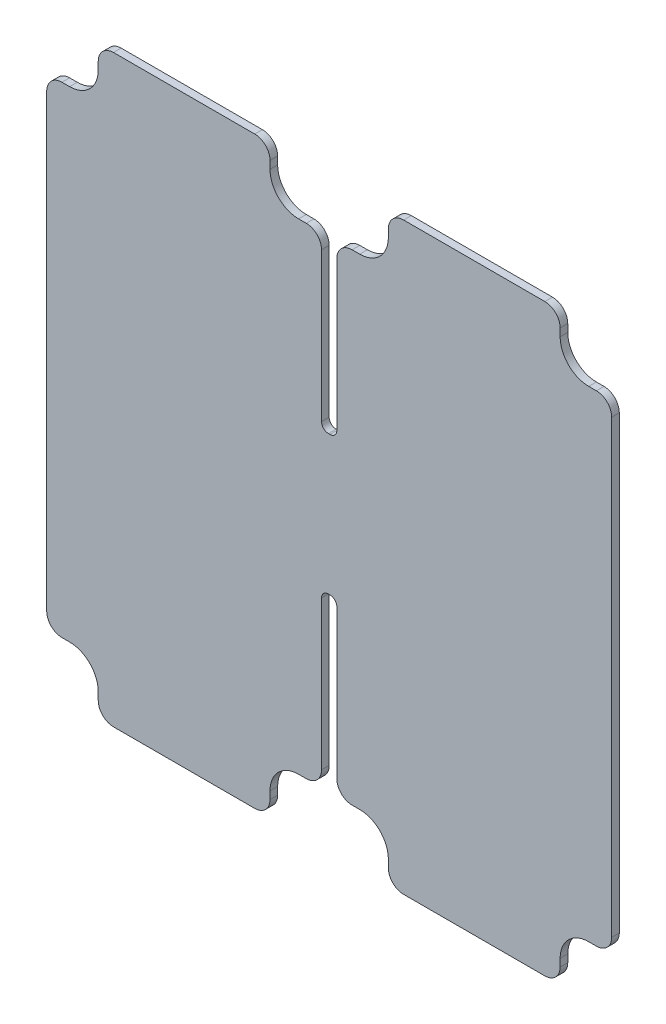
SolidWorks part; units mm, degrees
ref_plane "Front Plane" through (0, 0, 0) normal (0, 0, 1) x (1, 0, 0)
ref_plane "Top Plane" through (0, 0, 0) normal (0, 1, 0) x (1, 0, 0)
ref_plane "Right Plane" through (0, 0, 0) normal (1, 0, 0) x (0, 0, -1)
sketch "Model" plane through (0, 0, 0) normal (0, 0, 1) x (1, 0, 0)
  line L0 (3, 69.75) -> (2, 69.75)
  line L1 (6.75, 74.5) -> (6.75, 73.5)
  line L2 (29.25, 73.5) -> (29.25, 74.5)
  line L3 (34, 69.75) -> (33, 69.75)
  line L4 (33, 6.75) -> (34, 6.75)
  line L5 (29.25, 2) -> (29.25, 3)
  line L6 (6.75, 3) -> (6.75, 2)
  line L7 (2, 6.75) -> (3, 6.75)
  line L8 (36, 8.75) -> (36, 67.75)
  line L9 (8.75, 0) -> (27.25, 0)
  line L10 (0, 67.75) -> (0, 8.75)
  line L11 (27.25, 76.5) -> (8.75, 76.5)
  line L12 (41, 69.75) -> (40, 69.75)
  line L13 (44.75, 74.5) -> (44.75, 73.5)
  line L14 (67.25, 73.5) -> (67.25, 74.5)
  line L15 (72, 69.75) -> (71, 69.75)
  line L16 (71, 6.75) -> (72, 6.75)
  line L17 (67.25, 2) -> (67.25, 3)
  line L18 (44.75, 3) -> (44.75, 2)
  line L19 (40, 6.75) -> (41, 6.75)
  line L20 (74, 8.75) -> (74, 67.75)
  line L21 (46.75, 0) -> (65.25, 0)
  line L22 (38, 67.75) -> (38, 8.75)
  line L23 (65.25, 76.5) -> (46.75, 76.5)
  arc A0 (2, 69.7525) -> (2, 69.7475) centre (2, 69.75) ccw
  arc A1 (3, 69.7475) -> (3, 69.7525) centre (3, 69.75) ccw
  arc A2 (6.7475, 73.5) -> (6.7525, 73.5) centre (6.75, 73.5) ccw
  arc A3 (6.7525, 74.5) -> (6.7475, 74.5) centre (6.75, 74.5) ccw
  arc A4 (29.2525, 74.5) -> (29.2475, 74.5) centre (29.25, 74.5) ccw
  arc A5 (29.2475, 73.5) -> (29.2525, 73.5) centre (29.25, 73.5) ccw
  arc A6 (33, 69.7525) -> (33, 69.7475) centre (33, 69.75) ccw
  arc A7 (34, 69.7475) -> (34, 69.7525) centre (34, 69.75) ccw
  arc A8 (34, 6.7475) -> (34, 6.7525) centre (34, 6.75) ccw
  arc A9 (33, 6.7525) -> (33, 6.7475) centre (33, 6.75) ccw
  arc A10 (29.2525, 3) -> (29.2475, 3) centre (29.25, 3) ccw
  arc A11 (29.2475, 2) -> (29.2525, 2) centre (29.25, 2) ccw
  arc A12 (6.7475, 2) -> (6.7525, 2) centre (6.75, 2) ccw
  arc A13 (6.7525, 3) -> (6.7475, 3) centre (6.75, 3) ccw
  arc A14 (3, 6.7475) -> (3, 6.7525) centre (3, 6.75) ccw
  arc A15 (2, 6.7525) -> (2, 6.7475) centre (2, 6.75) ccw
  arc A16 (36.0025, 67.75) -> (35.9975, 67.75) centre (36, 67.75) ccw
  arc A17 (35.9975, 8.75) -> (36.0025, 8.75) centre (36, 8.75) ccw
  arc A18 (27.25, -0.0025) -> (27.25, 0.0025) centre (27.25, 0) ccw
  arc A19 (8.75, 0.0025) -> (8.75, -0.0025) centre (8.75, 0) ccw
  arc A20 (-0.0025, 8.75) -> (0.0025, 8.75) centre (0, 8.75) ccw
  arc A21 (0.0025, 67.75) -> (-0.0025, 67.75) centre (0, 67.75) ccw
  arc A22 (8.75, 76.5025) -> (8.75, 76.4975) centre (8.75, 76.5) ccw
  arc A23 (27.25, 76.4975) -> (27.25, 76.5025) centre (27.25, 76.5) ccw
  arc A24 (2, 69.75) -> (0, 67.75) centre (2, 67.75) ccw
  arc A25 (2, 69.7475) -> (2, 69.7525) centre (2, 69.75) ccw
  arc A26 (-0.0025, 67.75) -> (0.0025, 67.75) centre (0, 67.75) ccw
  arc A27 (3, 69.75) -> (6.75, 73.5) centre (2.9999, 73.5001) ccw
  arc A28 (3, 69.7525) -> (3, 69.7475) centre (3, 69.75) ccw
  arc A29 (6.7525, 73.5) -> (6.7475, 73.5) centre (6.75, 73.5) ccw
  arc A30 (8.75, 76.5) -> (6.75, 74.5) centre (8.75, 74.5) ccw
  arc A31 (8.75, 76.4975) -> (8.75, 76.5025) centre (8.75, 76.5) ccw
  arc A32 (6.7475, 74.5) -> (6.7525, 74.5) centre (6.75, 74.5) ccw
  arc A33 (29.25, 74.5) -> (27.25, 76.5) centre (27.25, 74.5) ccw
  arc A34 (29.2475, 74.5) -> (29.2525, 74.5) centre (29.25, 74.5) ccw
  arc A35 (27.25, 76.5025) -> (27.25, 76.4975) centre (27.25, 76.5) ccw
  arc A36 (29.25, 73.5) -> (33, 69.75) centre (33.0001, 73.5001) ccw
  arc A37 (29.2525, 73.5) -> (29.2475, 73.5) centre (29.25, 73.5) ccw
  arc A38 (33, 69.7475) -> (33, 69.7525) centre (33, 69.75) ccw
  arc A39 (36, 67.75) -> (34, 69.75) centre (34, 67.75) ccw
  arc A40 (35.9975, 67.75) -> (36.0025, 67.75) centre (36, 67.75) ccw
  arc A41 (34, 69.7525) -> (34, 69.7475) centre (34, 69.75) ccw
  arc A42 (34, 6.75) -> (36, 8.75) centre (34, 8.75) ccw
  arc A43 (34, 6.7525) -> (34, 6.7475) centre (34, 6.75) ccw
  arc A44 (36.0025, 8.75) -> (35.9975, 8.75) centre (36, 8.75) ccw
  arc A45 (33, 6.75) -> (29.25, 3) centre (33.0001, 2.9999) ccw
  arc A46 (33, 6.7475) -> (33, 6.7525) centre (33, 6.75) ccw
  arc A47 (29.2475, 3) -> (29.2525, 3) centre (29.25, 3) ccw
  arc A48 (27.25, 0) -> (29.25, 2) centre (27.25, 2) ccw
  arc A49 (27.25, 0.0025) -> (27.25, -0.0025) centre (27.25, 0) ccw
  arc A50 (29.2525, 2) -> (29.2475, 2) centre (29.25, 2) ccw
  arc A51 (6.75, 2) -> (8.75, 0) centre (8.75, 2) ccw
  arc A52 (6.7525, 2) -> (6.7475, 2) centre (6.75, 2) ccw
  arc A53 (8.75, -0.0025) -> (8.75, 0.0025) centre (8.75, 0) ccw
  arc A54 (6.75, 3) -> (3, 6.75) centre (2.9999, 2.9999) ccw
  arc A55 (6.7475, 3) -> (6.7525, 3) centre (6.75, 3) ccw
  arc A56 (3, 6.7525) -> (3, 6.7475) centre (3, 6.75) ccw
  arc A57 (0, 8.75) -> (2, 6.75) centre (2, 8.75) ccw
  arc A58 (0.0025, 8.75) -> (-0.0025, 8.75) centre (0, 8.75) ccw
  arc A59 (2, 6.7475) -> (2, 6.7525) centre (2, 6.75) ccw
  arc A60 (40, 69.7525) -> (40, 69.7475) centre (40, 69.75) ccw
  arc A61 (41, 69.7475) -> (41, 69.7525) centre (41, 69.75) ccw
  arc A62 (44.7475, 73.5) -> (44.7525, 73.5) centre (44.75, 73.5) ccw
  arc A63 (44.7525, 74.5) -> (44.7475, 74.5) centre (44.75, 74.5) ccw
  arc A64 (67.2525, 74.5) -> (67.2475, 74.5) centre (67.25, 74.5) ccw
  arc A65 (67.2475, 73.5) -> (67.2525, 73.5) centre (67.25, 73.5) ccw
  arc A66 (71, 69.7525) -> (71, 69.7475) centre (71, 69.75) ccw
  arc A67 (72, 69.7475) -> (72, 69.7525) centre (72, 69.75) ccw
  arc A68 (72, 6.7475) -> (72, 6.7525) centre (72, 6.75) ccw
  arc A69 (71, 6.7525) -> (71, 6.7475) centre (71, 6.75) ccw
  arc A70 (67.2525, 3) -> (67.2475, 3) centre (67.25, 3) ccw
  arc A71 (67.2475, 2) -> (67.2525, 2) centre (67.25, 2) ccw
  arc A72 (44.7475, 2) -> (44.7525, 2) centre (44.75, 2) ccw
  arc A73 (44.7525, 3) -> (44.7475, 3) centre (44.75, 3) ccw
  arc A74 (41, 6.7475) -> (41, 6.7525) centre (41, 6.75) ccw
  arc A75 (40, 6.7525) -> (40, 6.7475) centre (40, 6.75) ccw
  arc A76 (74.0025, 67.75) -> (73.9975, 67.75) centre (74, 67.75) ccw
  arc A77 (73.9975, 8.75) -> (74.0025, 8.75) centre (74, 8.75) ccw
  arc A78 (65.25, -0.0025) -> (65.25, 0.0025) centre (65.25, 0) ccw
  arc A79 (46.75, 0.0025) -> (46.75, -0.0025) centre (46.75, 0) ccw
  arc A80 (37.9975, 8.75) -> (38.0025, 8.75) centre (38, 8.75) ccw
  arc A81 (38.0025, 67.75) -> (37.9975, 67.75) centre (38, 67.75) ccw
  arc A82 (46.75, 76.5025) -> (46.75, 76.4975) centre (46.75, 76.5) ccw
  arc A83 (65.25, 76.4975) -> (65.25, 76.5025) centre (65.25, 76.5) ccw
  arc A84 (40, 69.75) -> (38, 67.75) centre (40, 67.75) ccw
  arc A85 (40, 69.7475) -> (40, 69.7525) centre (40, 69.75) ccw
  arc A86 (37.9975, 67.75) -> (38.0025, 67.75) centre (38, 67.75) ccw
  arc A87 (41, 69.75) -> (44.75, 73.5) centre (40.9999, 73.5001) ccw
  arc A88 (41, 69.7525) -> (41, 69.7475) centre (41, 69.75) ccw
  arc A89 (44.7525, 73.5) -> (44.7475, 73.5) centre (44.75, 73.5) ccw
  arc A90 (46.75, 76.5) -> (44.75, 74.5) centre (46.75, 74.5) ccw
  arc A91 (46.75, 76.4975) -> (46.75, 76.5025) centre (46.75, 76.5) ccw
  arc A92 (44.7475, 74.5) -> (44.7525, 74.5) centre (44.75, 74.5) ccw
  arc A93 (67.25, 74.5) -> (65.25, 76.5) centre (65.25, 74.5) ccw
  arc A94 (67.2475, 74.5) -> (67.2525, 74.5) centre (67.25, 74.5) ccw
  arc A95 (65.25, 76.5025) -> (65.25, 76.4975) centre (65.25, 76.5) ccw
  arc A96 (67.25, 73.5) -> (71, 69.75) centre (71.0001, 73.5001) ccw
  arc A97 (67.2525, 73.5) -> (67.2475, 73.5) centre (67.25, 73.5) ccw
  arc A98 (71, 69.7475) -> (71, 69.7525) centre (71, 69.75) ccw
  arc A99 (74, 67.75) -> (72, 69.75) centre (72, 67.75) ccw
  arc A100 (73.9975, 67.75) -> (74.0025, 67.75) centre (74, 67.75) ccw
  arc A101 (72, 69.7525) -> (72, 69.7475) centre (72, 69.75) ccw
  arc A102 (72, 6.75) -> (74, 8.75) centre (72, 8.75) ccw
  arc A103 (72, 6.7525) -> (72, 6.7475) centre (72, 6.75) ccw
  arc A104 (74.0025, 8.75) -> (73.9975, 8.75) centre (74, 8.75) ccw
  arc A105 (71, 6.75) -> (67.25, 3) centre (71.0001, 2.9999) ccw
  arc A106 (71, 6.7475) -> (71, 6.7525) centre (71, 6.75) ccw
  arc A107 (67.2475, 3) -> (67.2525, 3) centre (67.25, 3) ccw
  arc A108 (65.25, 0) -> (67.25, 2) centre (65.25, 2) ccw
  arc A109 (65.25, 0.0025) -> (65.25, -0.0025) centre (65.25, 0) ccw
  arc A110 (67.2525, 2) -> (67.2475, 2) centre (67.25, 2) ccw
  arc A111 (44.75, 2) -> (46.75, 0) centre (46.75, 2) ccw
  arc A112 (44.7525, 2) -> (44.7475, 2) centre (44.75, 2) ccw
  arc A113 (46.75, -0.0025) -> (46.75, 0.0025) centre (46.75, 0) ccw
  arc A114 (44.75, 3) -> (41, 6.75) centre (40.9999, 2.9999) ccw
  arc A115 (44.7475, 3) -> (44.7525, 3) centre (44.75, 3) ccw
  arc A116 (41, 6.7525) -> (41, 6.7475) centre (41, 6.75) ccw
  arc A117 (38, 8.75) -> (40, 6.75) centre (40, 8.75) ccw
  arc A118 (38.0025, 8.75) -> (37.9975, 8.75) centre (38, 8.75) ccw
  arc A119 (40, 6.7475) -> (40, 6.7525) centre (40, 6.75) ccw
sketch "Sketch2" plane through (0, 0, 0) normal (0, 0, 1) x (1, 0, 0)
  line L0 (36, 8.75) -> (36, 67.75) construction
  line L1 (38, 67.75) -> (38, 8.75) construction
  line L2 (41, 69.75) -> (40, 69.75) construction
  line L3 (44.75, 74.5) -> (44.75, 73.5) construction
  line L4 (65.25, 76.5) -> (46.75, 76.5) construction
  line L5 (67.25, 73.5) -> (67.25, 74.5) construction
  line L6 (72, 69.75) -> (71, 69.75) construction
  line L7 (74, 8.75) -> (74, 67.75) construction
  line L8 (33, 6.75) -> (34, 6.75) construction
  line L9 (40, 6.75) -> (41, 6.75) construction
  line L10 (44.75, 3) -> (44.75, 2) construction
  line L11 (46.75, 0) -> (65.25, 0) construction
  line L12 (67.25, 2) -> (67.25, 3) construction
  line L13 (71, 6.75) -> (72, 6.75) construction
  line L14 (29.25, 2) -> (29.25, 3) construction
  line L15 (8.75, 0) -> (27.25, 0) construction
  line L16 (6.75, 3) -> (6.75, 2) construction
  line L17 (2, 6.75) -> (3, 6.75) construction
  line L18 (34, 69.75) -> (33, 69.75) construction
  line L19 (29.25, 73.5) -> (29.25, 74.5) construction
  line L20 (27.25, 76.5) -> (8.75, 76.5) construction
  line L21 (6.75, 74.5) -> (6.75, 73.5) construction
  line L22 (3, 69.75) -> (2, 69.75) construction
  line L23 (0, 67.75) -> (0, 8.75) construction
  line L24 (36, 8.75) -> (36, 67.75) construction
  line L25 (38, 67.75) -> (38, 8.75) construction
  line L26 (41, 69.75) -> (40, 69.75)
  line L27 (44.75, 74.5) -> (44.75, 73.5)
  line L28 (65.25, 76.5) -> (46.75, 76.5)
  line L29 (67.25, 73.5) -> (67.25, 74.5)
  line L30 (72, 69.75) -> (71, 69.75)
  line L31 (74, 8.75) -> (74, 67.75)
  line L32 (33, 6.75) -> (34, 6.75)
  line L33 (40, 6.75) -> (41, 6.75)
  line L34 (44.75, 3) -> (44.75, 2)
  line L35 (46.75, 0) -> (65.25, 0)
  line L36 (67.25, 2) -> (67.25, 3)
  line L37 (71, 6.75) -> (72, 6.75)
  line L38 (29.25, 2) -> (29.25, 3)
  line L39 (8.75, 0) -> (27.25, 0)
  line L40 (6.75, 3) -> (6.75, 2)
  line L41 (2, 6.75) -> (3, 6.75)
  line L42 (34, 69.75) -> (33, 69.75)
  line L43 (29.25, 73.5) -> (29.25, 74.5)
  line L44 (27.25, 76.5) -> (8.75, 76.5)
  line L45 (6.75, 74.5) -> (6.75, 73.5)
  line L46 (3, 69.75) -> (2, 69.75)
  line L47 (0, 67.75) -> (0, 8.75)
  line L48 (0, 38.25) -> (74, 38.25) construction
  line L49 (38, 67.75) -> (38, 48.25)
  line L50 (37.1, 47.35) -> (36.9, 47.35)
  line L51 (36, 48.25) -> (36, 67.75)
  line L52 (37.1, 29.15) -> (36.9, 29.15)
  line L53 (38, 8.75) -> (38, 28.25)
  line L54 (36, 28.25) -> (36, 8.75)
  line L55 (0, 0) -> (2.3384, 0)
  line L56 (2.3384, 0) -> (0, 2.9999)
  line L57 (0, 2.9999) -> (0, 0)
  arc A0 (40, 69.75) -> (38, 67.75) centre (40, 67.75) ccw construction
  arc A1 (41, 69.75) -> (44.75, 73.5) centre (40.9999, 73.5001) ccw construction
  arc A2 (46.75, 76.5) -> (44.75, 74.5) centre (46.75, 74.5) ccw construction
  arc A3 (67.25, 74.5) -> (65.25, 76.5) centre (65.25, 74.5) ccw construction
  arc A4 (67.25, 73.5) -> (71, 69.75) centre (71.0001, 73.5001) ccw construction
  arc A5 (74, 67.75) -> (72, 69.75) centre (72, 67.75) ccw construction
  arc A6 (34, 6.75) -> (36, 8.75) centre (34, 8.75) ccw construction
  arc A7 (38, 8.75) -> (40, 6.75) centre (40, 8.75) ccw construction
  arc A8 (44.75, 3) -> (41, 6.75) centre (40.9999, 2.9999) ccw construction
  arc A9 (44.75, 2) -> (46.75, 0) centre (46.75, 2) ccw construction
  arc A10 (65.25, 0) -> (67.25, 2) centre (65.25, 2) ccw construction
  arc A11 (71, 6.75) -> (67.25, 3) centre (71.0001, 2.9999) ccw construction
  arc A12 (72, 6.75) -> (74, 8.75) centre (72, 8.75) ccw construction
  arc A13 (33, 6.75) -> (29.25, 3) centre (33.0001, 2.9999) ccw construction
  arc A14 (27.25, 0) -> (29.25, 2) centre (27.25, 2) ccw construction
  arc A15 (6.75, 2) -> (8.75, 0) centre (8.75, 2) ccw construction
  arc A16 (6.75, 3) -> (3, 6.75) centre (2.9999, 2.9999) ccw construction
  arc A17 (0, 8.75) -> (2, 6.75) centre (2, 8.75) ccw construction
  arc A18 (36, 67.75) -> (34, 69.75) centre (34, 67.75) ccw construction
  arc A19 (29.25, 73.5) -> (33, 69.75) centre (33.0001, 73.5001) ccw construction
  arc A20 (29.25, 74.5) -> (27.25, 76.5) centre (27.25, 74.5) ccw construction
  arc A21 (8.75, 76.5) -> (6.75, 74.5) centre (8.75, 74.5) ccw construction
  arc A22 (3, 69.75) -> (6.75, 73.5) centre (2.9999, 73.5001) ccw construction
  arc A23 (2, 69.75) -> (0, 67.75) centre (2, 67.75) ccw construction
  arc A24 (40, 69.75) -> (38, 67.75) centre (40, 67.75) ccw
  arc A25 (41, 69.75) -> (44.75, 73.5) centre (40.9999, 73.5001) ccw
  arc A26 (46.75, 76.5) -> (44.75, 74.5) centre (46.75, 74.5) ccw
  arc A27 (67.25, 74.5) -> (65.25, 76.5) centre (65.25, 74.5) ccw
  arc A28 (67.25, 73.5) -> (71, 69.75) centre (71.0001, 73.5001) ccw
  arc A29 (74, 67.75) -> (72, 69.75) centre (72, 67.75) ccw
  arc A30 (34, 6.75) -> (36, 8.75) centre (34, 8.75) ccw
  arc A31 (38, 8.75) -> (40, 6.75) centre (40, 8.75) ccw
  arc A32 (44.75, 3) -> (41, 6.75) centre (40.9999, 2.9999) ccw
  arc A33 (44.75, 2) -> (46.75, 0) centre (46.75, 2) ccw
  arc A34 (65.25, 0) -> (67.25, 2) centre (65.25, 2) ccw
  arc A35 (71, 6.75) -> (67.25, 3) centre (71.0001, 2.9999) ccw
  arc A36 (72, 6.75) -> (74, 8.75) centre (72, 8.75) ccw
  arc A37 (33, 6.75) -> (29.25, 3) centre (33.0001, 2.9999) ccw
  arc A38 (27.25, 0) -> (29.25, 2) centre (27.25, 2) ccw
  arc A39 (6.75, 2) -> (8.75, 0) centre (8.75, 2) ccw
  arc A40 (6.75, 3) -> (3, 6.75) centre (2.9999, 2.9999) ccw
  arc A41 (0, 8.75) -> (2, 6.75) centre (2, 8.75) ccw
  arc A42 (36, 67.75) -> (34, 69.75) centre (34, 67.75) ccw
  arc A43 (29.25, 73.5) -> (33, 69.75) centre (33.0001, 73.5001) ccw
  arc A44 (29.25, 74.5) -> (27.25, 76.5) centre (27.25, 74.5) ccw
  arc A45 (8.75, 76.5) -> (6.75, 74.5) centre (8.75, 74.5) ccw
  arc A46 (3, 69.75) -> (6.75, 73.5) centre (2.9999, 73.5001) ccw
  arc A47 (2, 69.75) -> (0, 67.75) centre (2, 67.75) ccw
  arc A48 (38, 48.25) -> (37.1, 47.35) centre (37.1, 48.25) cw
  arc A49 (36, 48.25) -> (36.9, 47.35) centre (36.9, 48.25) ccw
  arc A50 (36, 28.25) -> (36.9, 29.15) centre (36.9, 28.25) cw
  arc A51 (38, 28.25) -> (37.1, 29.15) centre (37.1, 28.25) ccw
  point P23 (38, 47.35)
  point P31 (36, 47.35)
  point P57 (36, 67.7302)
  dimension "D1" = 0.9
  dimension "D2" = 10
extrude "Boss-Extrude1" add sketch "Sketch2" along normal blind 1 contours A51 L53 A31 L33 A32 L34 A33 L35 A34 L36 A35 L37 A36 L31 A29 L30 A28 L29 A27 L28 A26 L27 A25 L26 A24 L49 A48 L50 A49 L51 A42 L42 A43 L43 A44 L44 A45 L45 A46 L46 A47 L47 A41 L41 A40 L40 A39 L39 A38 L38 A37
